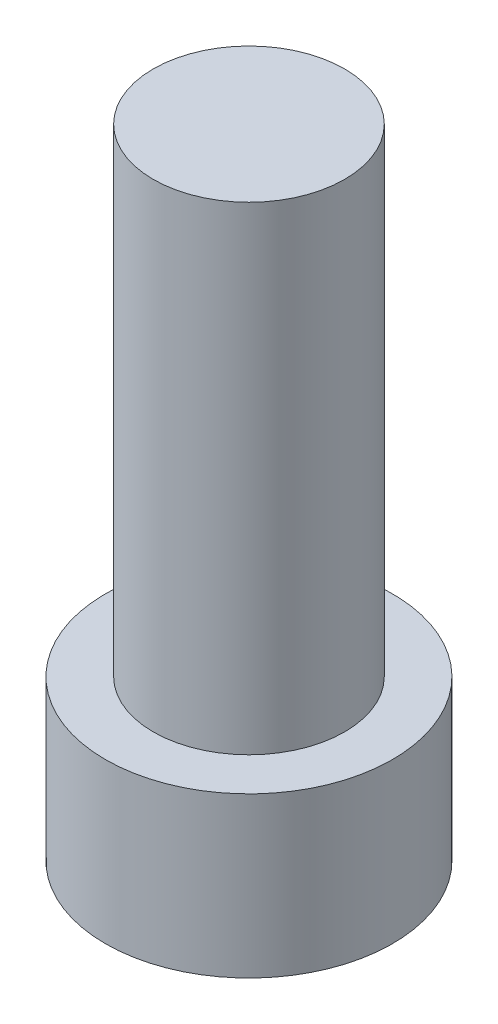
SolidWorks part; units mm, degrees
ref_plane "Спереди" through (0, 0, 0) normal (0, 0, 1) x (1, 0, 0)
ref_plane "Сверху" through (0, 0, 0) normal (0, 1, 0) x (1, 0, 0)
ref_plane "Справа" through (0, 0, 0) normal (1, 0, 0) x (0, 0, -1)
sketch "Эскиз1" plane through (0, 0, 0) normal (0, 1, 0) x (1, 0, 0)
  circle A0 centre (0, 0) radius 4.5
extrude "Бобышка-Вытянуть1" add sketch "Эскиз1" along normal blind 20
sketch "Эскиз2" plane through (0, 20, 0) normal (0, 1, 0) x (1, 0, 0)
  circle A0 centre (0, 0) radius 3
  circle A1 centre (0, 0) radius 4.5
extrude "Вырез-Вытянуть1" cut sketch "Эскиз2" against normal blind 15
sketch "Эскиз3" plane through (0, 0, 0) normal (0, -1, 0) x (1, 0, 0)
  circle A0 centre (0, 0) radius 1.5875
  dimension "D1" = 3.175
extrude "Вырез-Вытянуть2" cut sketch "Эскиз3" against normal blind 15
